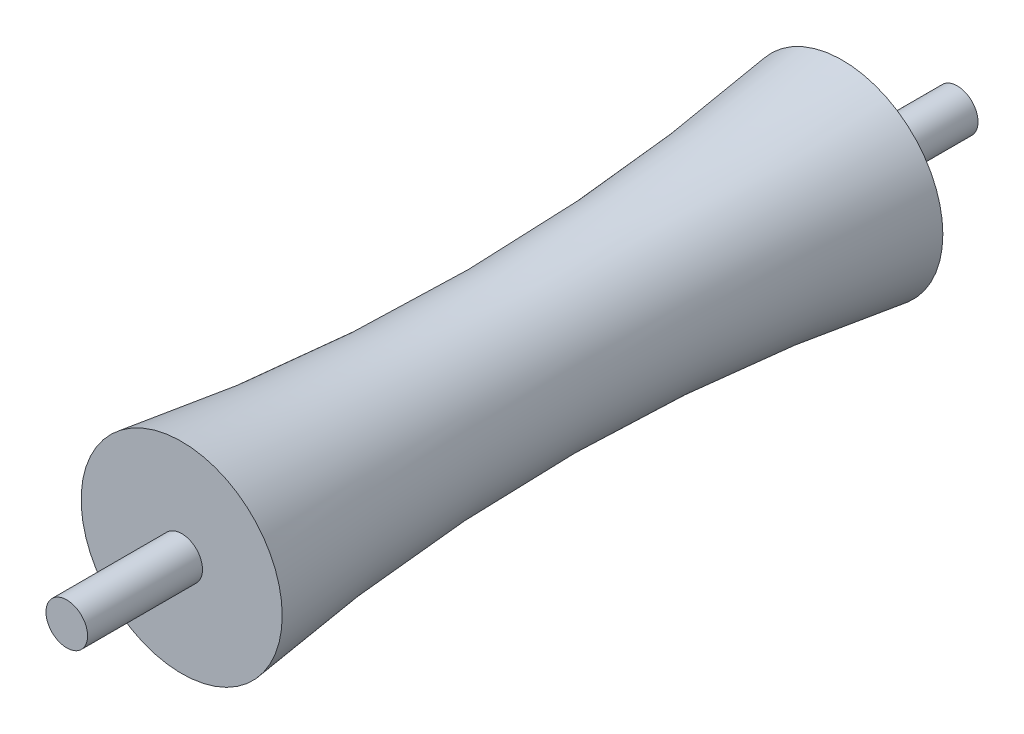
SolidWorks part; units mm, degrees
ref_plane "Front Plane" through (0, 0, 0) normal (0, 0, 1) x (1, 0, 0)
ref_plane "Top Plane" through (0, 0, 0) normal (0, 1, 0) x (1, 0, 0)
ref_plane "Right Plane" through (0, 0, 0) normal (1, 0, 0) x (0, 0, -1)
sketch "Sketch1" plane through (0, 0, 0) normal (0, 1, 0) x (1, 0, 0)
  line L0 (0, 0) -> (0, 46)
  line L1 (0, 46) -> (7, 46)
  line L2 (0, 0) -> (7, 0)
  arc A0 (7, 0) -> (7, 46) centre (155.2262, 23) cw
  dimension "D1" = 46
  dimension "D2" = 7
  dimension "D3" = 7
revolve "Revolve1" add sketch "Sketch1" angle 360 about L0
sketch "Sketch2" plane through (0, 0, 0) normal (0, 0, 1) x (1, 0, 0)
  circle A0 centre (0, 0) radius 1.45
extrude "Boss-Extrude1" add sketch "Sketch2" along normal blind 8
sketch "Sketch3" plane through (0, 0, -46) normal (0, 0, -1) x (-1, 0, 0)
  circle A0 centre (0, 0) radius 1.45
extrude "Boss-Extrude2" add sketch "Sketch3" along normal blind 8
